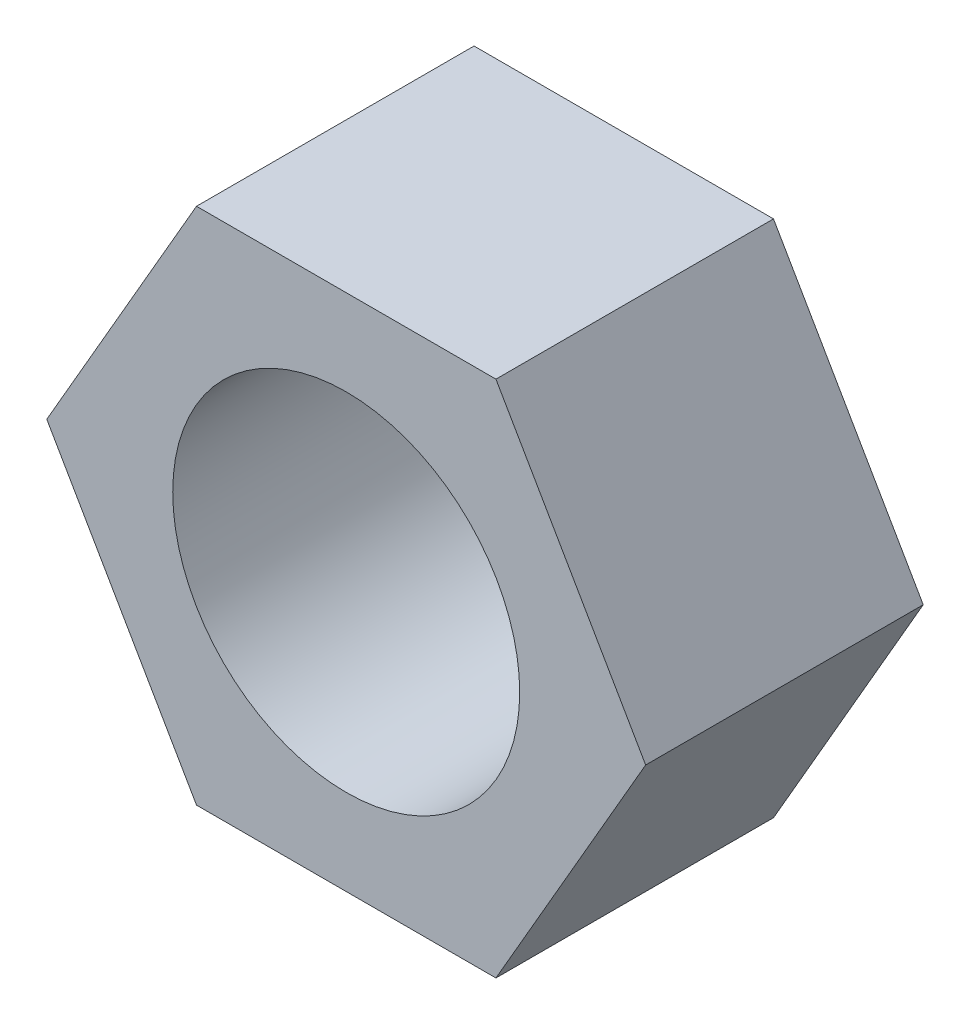
SolidWorks part; units mm, degrees
ref_plane "前视基准面" through (0, 0, 0) normal (0, 0, 1) x (1, 0, 0)
ref_plane "上视基准面" through (0, 0, 0) normal (0, 1, 0) x (1, 0, 0)
ref_plane "右视基准面" through (0, 0, 0) normal (1, 0, 0) x (0, 0, -1)
other "Configuration Table"
sketch "草图1" plane through (0, 0, 0) normal (0, 0, 1) x (1, 0, 0)
  line L1 (2.5891, 0) -> (1.2945, 2.2422)
  line L2 (1.2945, 2.2422) -> (-1.2945, 2.2422)
  line L3 (-1.2945, 2.2422) -> (-2.5891, 0)
  line L4 (-2.5891, 0) -> (-1.2945, -2.2422)
  line L5 (-1.2945, -2.2422) -> (1.2945, -2.2422)
  line L6 (1.2945, -2.2422) -> (2.5891, 0)
  circle A0 centre (0, 0) radius 2.2422 construction
  circle A1 centre (0, 0) radius 1.5
  dimension "D1" = 3
extrude "凸台-拉伸1" add sketch "草图1" along normal blind 2.4
